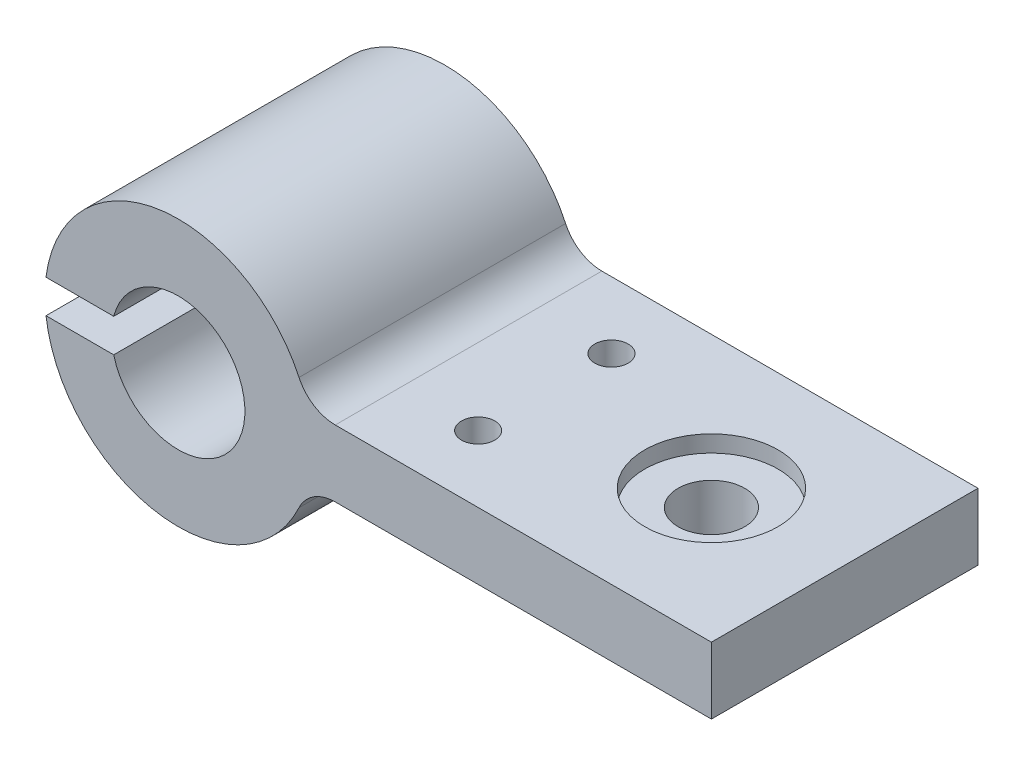
SolidWorks part; units mm, degrees
ref_plane "Front Plane" through (0, 0, 0) normal (0, 0, 1) x (1, 0, 0)
ref_plane "Top Plane" through (0, 0, 0) normal (0, 1, 0) x (1, 0, 0)
ref_plane "Right Plane" through (0, 0, 0) normal (1, 0, 0) x (0, 0, -1)
sketch "Sketch1" plane through (0, 0, 0) normal (0, 0, 1) x (1, 0, 0)
  line L0 (0, 42.2544) -> (0, -59.0752) construction
  line L2 (0, 6.35) -> (101.6, 6.35)
  line L3 (0, 6.35) -> (0, -6.35)
  line L4 (0, -6.35) -> (101.6, -6.35)
  line L5 (101.6, 6.35) -> (101.6, -6.35)
  circle A0 centre (0, 0) radius 25.4
  circle A1 centre (29.9192, -13.97) radius 7.62
  circle A2 centre (29.9192, 13.97) radius 7.62
  dimension "D1" = 50.8
  dimension "D5" = 15.24
  dimension "D6" = 15.24
  dimension "D2" = 101.6
  dimension "D3" = 12.7
  dimension "D4" = 6.35
extrude "Boss-Extrude2" add sketch "Sketch1" along normal blind 50.8 contours A1 L4 A0 | A2 A0 L2 | A0 L4 L5 L2 | L4 L0 A0 | L4 A0 L2 L3 | A0 L0 L2 | L0 A0 L3
sketch "Sketch2" plane through (0, 6.35, 0) normal (0, 1, 0) x (1, 0, 0)
  line L0 (29.9192, 0) -> (101.6, 0) construction
  line L1 (101.6, -50.8) -> (101.6, 0) construction
  circle A0 centre (76.2, -25.4) radius 12.7
  dimension "D2" = 25.4
  dimension "D1" = 25.4
  dimension "D3" = 25.4
extrude "Cut-Extrude1" cut sketch "Sketch2" against normal blind 3.175
sketch "Sketch3" plane through (0, 3.175, 0) normal (0, 1, 0) x (1, 0, 0)
  circle A0 centre (76.2, -25.4) radius 6.35
  circle A1 centre (76.2, -25.4) radius 12.7 construction
  dimension "D1" = 12.7
extrude "Cut-Extrude2" cut sketch "Sketch3" against normal through all
sketch "Sketch4" plane through (0, 0, 50.8) normal (0, 0, 1) x (1, 0, 0)
  line L1 (-25.4, 3.175) -> (0, 3.175)
  line L2 (-25.4, 3.175) -> (-25.4, -3.175)
  line L3 (-25.4, -3.175) -> (0, -3.175)
  line L4 (0, 3.175) -> (0, -3.175)
  circle A0 centre (0, 0) radius 12.7
  arc A1 (23.0148, 10.7462) -> (23.0148, -10.7462) centre (0, 0) ccw construction
  arc M7 (23.0148, 10.7462) -> (23.0148, -10.7462) centre (0, 0) ccw
  dimension "D3" = 25.4
  dimension "D1" = 6.35
  dimension "D2" = 25.4
extrude "Cut-Extrude3" cut sketch "Sketch4" along normal through all and the other way through all contours A0 L1 L3 M7 | L3 A0 L1 L4 | L1 A0 L3 L4
sketch "Sketch5" plane through (0, 6.35, 0) normal (0, 1, 0) x (1, 0, 0)
  line L0 (-52.8052, -25.4) -> (135.1848, -25.4) construction
  line L1 (29.9192, -50.8) -> (101.6, -50.8) construction
  line L2 (29.9192, 0) -> (101.6, 0) construction
  line L3 (101.6, -50.8) -> (101.6, 0) construction
  circle A0 centre (44.45, -12.7) radius 3.175
  circle A1 centre (44.45, -38.1) radius 3.175
  dimension "D2" = 6.35
  dimension "D1" = 25.4
  dimension "D3" = 12.7
  dimension "D4" = 57.15
extrude "Cut-Extrude4" cut sketch "Sketch5" against normal through all
